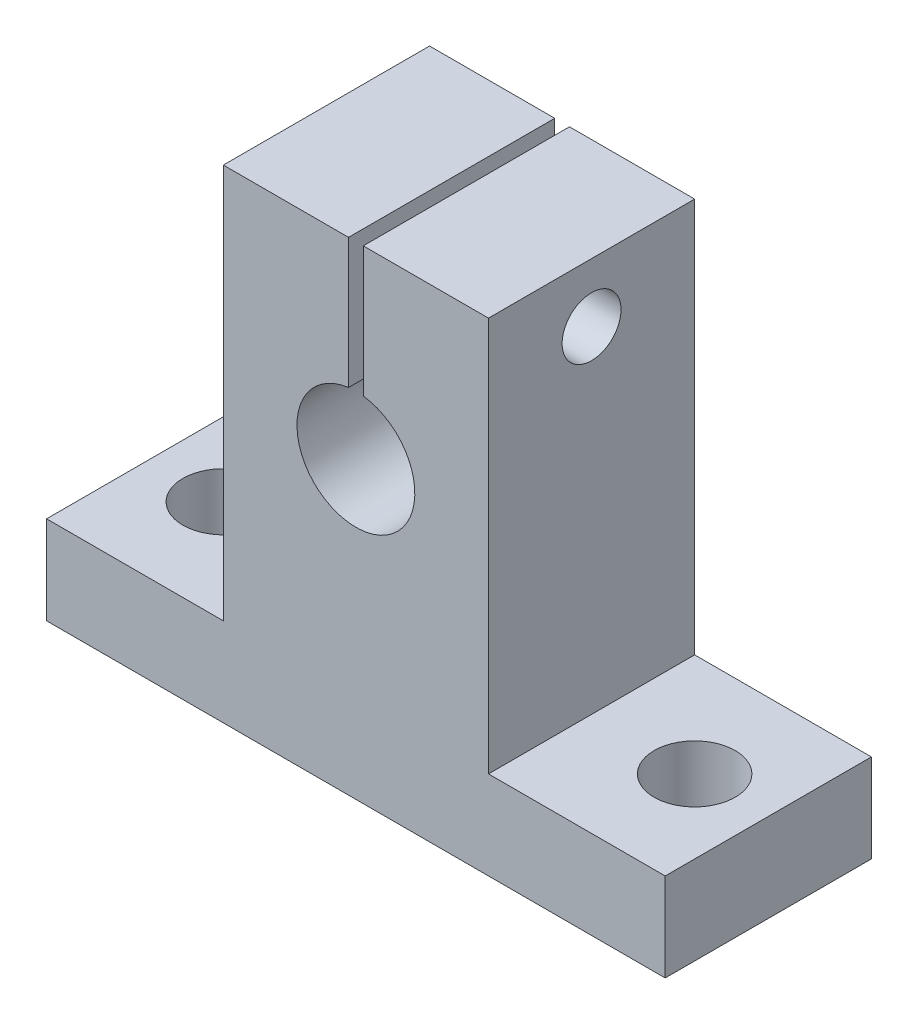
SolidWorks part; units mm, degrees
ref_plane "Front" through (0, 0, 0) normal (0, 0, 1) x (1, 0, 0)
ref_plane "Top" through (0, 0, 0) normal (0, 1, 0) x (1, 0, 0)
ref_plane "Right" through (0, 0, 0) normal (1, 0, 0) x (0, 0, -1)
sketch "Sketch1" plane through (0, 0, 0) normal (0, 0, 1) x (1, 0, 0)
  line L0 (0, 32.8) -> (0, -11.1975) construction
  line L1 (-21, 0) -> (21, 0)
  line L2 (-21, 0) -> (-21, 6)
  line L3 (-21, 6) -> (-9, 6)
  line L4 (21, 0) -> (21, 6)
  line L5 (9, 6) -> (21, 6)
  line L7 (-9, 6) -> (-9, 32.8)
  line L8 (-9, 32.8) -> (9, 32.8)
  line L9 (9, 6) -> (9, 32.8)
  circle A0 centre (0, 20) radius 4
  dimension "D4" = 8
  dimension "D1" = 6
  dimension "D2" = 42
  dimension "D3" = 18
  dimension "D5" = 32.8
  dimension "20" = 20
extrude "Boss-Extrude1" add sketch "Sketch1" along normal blind 14
sketch "Sketch2" plane through (9, 0, 0) normal (1, 0, 0) x (0, 0, -1)
  line L0 (-14, 32.8) -> (0, 32.8) construction
  line L1 (-7, 32.8) -> (-7, 14.0812) construction
  circle A0 centre (-7, 28.8) radius 2
  dimension "D1" = 4
  dimension "D2" = 4
sketch "Sketch3" plane through (0, 0, 14) normal (0, 0, 1) x (1, 0, 0)
  line L0 (9, 32.8) -> (-9, 32.8) construction
  line L1 (-0.5, 32.8) -> (0.5, 32.8)
  line L2 (-0.5, 32.8) -> (-0.5, 21.0098)
  line L3 (-0.5, 21.0098) -> (0.5, 21.0098)
  line L4 (0.5, 32.8) -> (0.5, 21.0098)
  line L5 (0, 32.8) -> (0, 12.111) construction
  dimension "D1" = 1
extrude "Cut-Extrude1" cut sketch "Sketch3" against normal blind 19 contours L4 L3 L2 L1
extrude "Cut-Extrude3" cut sketch "Sketch2" against normal blind 31 contours A0
sketch "Sketch5" plane through (0, 6, 0) normal (0, 1, 0) x (1, 0, 0)
  line L0 (0, 7.6779) -> (0, -23.3122) construction
  line L1 (21, -7) -> (-21, -7) construction
  line L4 (21, -14) -> (21, 0) construction
  line L5 (-21, -14) -> (-21, 0) construction
  circle A0 centre (16, -7) radius 2.75
  circle A1 centre (-16, -7) radius 2.75
  dimension "D1" = 32
  dimension "D2" = 5.5
extrude "Cut-Extrude5" cut sketch "Sketch5" against normal blind 22
